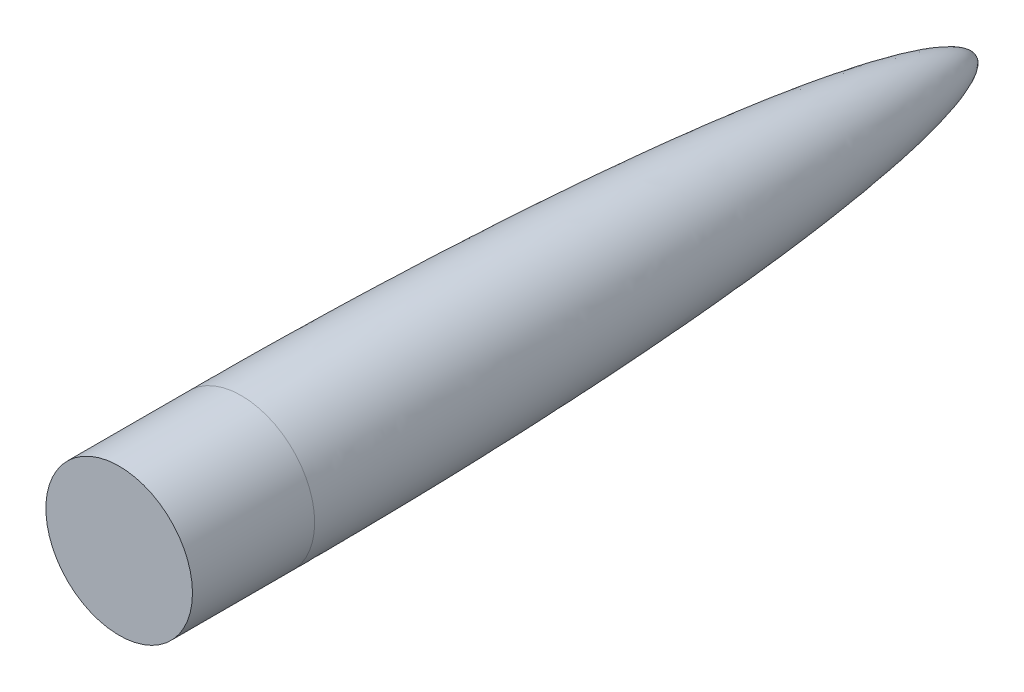
SolidWorks part; units mm, degrees
ref_plane "Front Plane" through (0, 0, 0) normal (0, 0, 1) x (1, 0, 0)
ref_plane "Top Plane" through (0, 0, 0) normal (0, 1, 0) x (1, 0, 0)
ref_plane "Right Plane" through (0, 0, 0) normal (1, 0, 0) x (0, 0, -1)
sketch "Sketch1" plane through (0, 0, 0) normal (1, 0, 0) x (0, 0, -1)
  line L0 (0, 76.2) -> (0, 0)
  line L1 (0, 0) -> (762, 0)
  spline S0 degree 4 poles (-76.206, 75.818) (-73.7924, 75.842) (-69.1095, 75.8878) (-61.8352, 75.9506) (-52.4796, 76.0222) (-42.7317, 76.0818) (-33.5435, 76.1295) (-23.4765, 76.1653) (-14.8601, 76.1891) (-2.1195, 76.2027) (4.6933, 76.2004) (14.8924, 76.1884) (21.4788, 76.1696) (29.5225, 76.1458) (39.5983, 76.101) (53.0526, 76.0219) (68.0651, 75.9013) (83.2698, 75.7503) (98.3627, 75.5687) (113.5218, 75.3563) (128.6402, 75.1127) (143.7824, 74.8379) (158.9093, 74.5313) (174.0444, 74.1926) (189.1734, 73.8213) (204.3047, 73.4171) (219.4333, 72.9792) (238.3438, 72.3893) (261.0337, 71.6116) (295.064, 70.3106) (340.4253, 68.2741) (393.3241, 65.4219) (453.7347, 61.4082) (514.0796, 56.4894) (566.7908, 51.1756) (611.8621, 45.6279) (647.3879, 40.3334) (670.6452, 36.2991) (689.1358, 32.5948) (703.1566, 29.4225) (714.6153, 26.537) (726.4007, 23.1565) (737.1125, 19.495) (745.7726, 15.8394) (752.0021, 12.4343) (755.6094, 9.9401) (757.8305, 8.0322) (759.2714, 6.5017) (760.2601, 5.2033) (760.928, 4.0959) (761.3715, 3.1467) (761.7674, 2.0148) (761.9434, 1.1485) (761.9994, 0.4866) (762, 0) knots 0 0 0 0 0 0.011201 0.022402 0.033603 0.044804 0.056005 0.067206 0.078407 0.089608 0.107406 0.111856 0.116305 0.125204 0.143003 0.160801 0.1786 0.196398 0.214196 0.231995 0.249793 0.267591 0.28539 0.303188 0.320987 0.338785 0.356583 0.374382 0.409978 0.445575 0.516769 0.587962 0.659156 0.730349 0.801543 0.837139 0.872736 0.899285 0.912559 0.925833 0.940347 0.954861 0.970211 0.979055 0.984498 0.988199 0.990804 0.992803 0.994368 0.995862 0.996875 0.997722 1 1 1 1 1 construction
  spline S1 degree 4 poles (0, 76.2) (3.4448, 76.2) (7.7076, 76.1969) (14.8924, 76.1884) (21.4788, 76.1696) (29.5225, 76.1458) (39.5983, 76.101) (53.0526, 76.0219) (68.0651, 75.9013) (83.2698, 75.7503) (98.3627, 75.5687) (113.5218, 75.3563) (128.6402, 75.1127) (143.7824, 74.8379) (158.9093, 74.5313) (174.0444, 74.1926) (189.1734, 73.8213) (204.3047, 73.4171) (219.4333, 72.9792) (238.3438, 72.3893) (261.0337, 71.6116) (295.064, 70.3106) (340.4253, 68.2741) (393.3241, 65.4219) (453.7347, 61.4082) (514.0796, 56.4894) (566.7908, 51.1756) (611.8621, 45.6279) (647.3879, 40.3334) (670.6452, 36.2991) (689.1358, 32.5948) (703.1566, 29.4225) (714.6153, 26.537) (726.4007, 23.1565) (737.1125, 19.495) (745.7726, 15.8394) (752.0021, 12.4343) (755.6094, 9.9401) (757.8305, 8.0322) (759.2714, 6.5017) (760.2601, 5.2033) (760.928, 4.0959) (761.3715, 3.1467) (761.7674, 2.0148) (761.9434, 1.1485) (761.9994, 0.4866) (762, 0) knots 0.089608 0.089608 0.089608 0.089608 0.089608 0.107406 0.111856 0.116305 0.125204 0.143003 0.160801 0.1786 0.196398 0.214196 0.231995 0.249793 0.267591 0.28539 0.303188 0.320987 0.338785 0.356583 0.374382 0.409978 0.445575 0.516769 0.587962 0.659156 0.730349 0.801543 0.837139 0.872736 0.899285 0.912559 0.925833 0.940347 0.954861 0.970211 0.979055 0.984498 0.988199 0.990804 0.992803 0.994368 0.995862 0.996875 0.997722 1 1 1 1 1
ref_axis "Axis1" through (0, 0, -480.06) along (0, 0, 1)
revolve "Revolve1" add sketch "Sketch1" angle 360 about axis through (0, 0, -480.06) along (0, 0, 1)
sketch "Sketch2" plane through (0, 0, 0) normal (0, 0, 1) x (1, 0, 0)
  circle A0 centre (0, 0) radius 76.2
  dimension "D1" = 152.4
extrude "Boss-Extrude1" add sketch "Sketch2" along normal blind 127
equation "\"BodyTubeRadius\"= 3in"
equation "\"ratio\"= 5"
equation "\"NoseConeLength\"= \"ratio\" * 2 * \"BodyTubeRadius\""
equation "\"D1@Sketch2\"=2*\"BodyTubeRadius\""
equation "\"BodyTubeLength\"=5"
